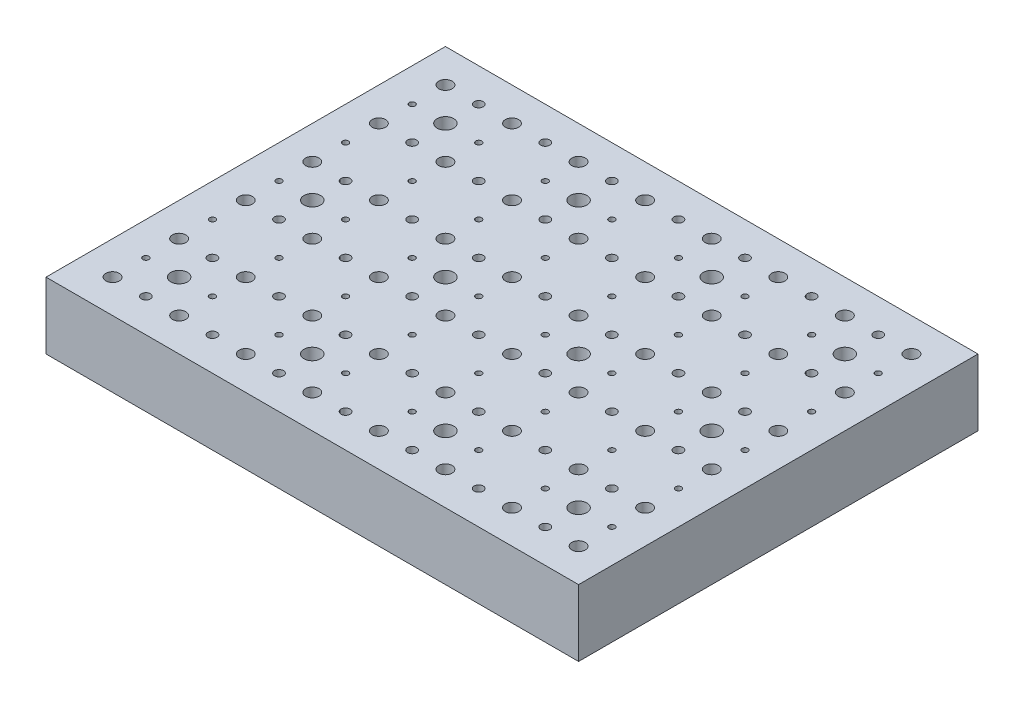
SolidWorks part; units mm, degrees
ref_plane "Front Plane" through (0, 0, 0) normal (0, 0, 1) x (1, 0, 0)
ref_plane "Top Plane" through (0, 0, 0) normal (0, 1, 0) x (1, 0, 0)
ref_plane "Right Plane" through (0, 0, 0) normal (1, 0, 0) x (0, 0, -1)
sketch "Sketch1" plane through (0, 0, 0) normal (0, 1, 0) x (1, 0, 0)
  line L1 (101.6, -76.2) -> (-101.6, -76.2)
  line L2 (101.6, -76.2) -> (101.6, 76.2)
  line L3 (101.6, 76.2) -> (-101.6, 76.2)
  line L4 (-101.6, -76.2) -> (-101.6, 76.2)
  line L5 (101.6, -76.2) -> (-101.6, 76.2) construction
  line L6 (101.6, 76.2) -> (-101.6, -76.2) construction
  point P0 (0, 0)
  dimension "D1" = 203.2
  dimension "D2" = 152.4
extrude "Boss-Extrude1" add sketch "Sketch1" against normal blind 25.4
hole_wizard "1/4-20 Tapped Hole2" positions "Sketch2" profile "Sketch3" tap size "1/4-20" standard "ANSI Inch" end condition through all
sketch "Sketch2" plane through (0, 0, 0) normal (0, 1, 0) x (1, 0, 0)
  line L0 (-12.7, 12.7) -> (0, 0) construction
  line L1 (0, 0) -> (-12.7, -12.7) construction
  line L3 (12.7, 12.7) -> (0, 0) construction
  line L4 (0, 0) -> (12.7, -12.7) construction
  point P0 (-88.9, 63.5)
  point P9 (-63.5, 63.5)
  point P10 (-38.1, 63.5)
  point P11 (-12.7, 63.5)
  point P12 (12.7, 63.5)
  point P13 (38.1, 63.5)
  point P14 (63.5, 63.5)
  point P15 (88.9, 63.5)
  point P16 (-63.5, 38.1)
  point P17 (-38.1, 38.1)
  point P18 (-12.7, 38.1)
  point P19 (12.7, 38.1)
  point P20 (38.1, 38.1)
  point P21 (63.5, 38.1)
  point P22 (88.9, 38.1)
  point P23 (-63.5, 12.7)
  point P24 (-38.1, 12.7)
  point P25 (-12.7, 12.7)
  point P26 (12.7, 12.7)
  point P27 (38.1, 12.7)
  point P28 (63.5, 12.7)
  point P29 (88.9, 12.7)
  point P30 (-63.5, -12.7)
  point P31 (-38.1, -12.7)
  point P32 (-12.7, -12.7)
  point P33 (12.7, -12.7)
  point P34 (38.1, -12.7)
  point P35 (63.5, -12.7)
  point P36 (88.9, -12.7)
  point P37 (-63.5, -38.1)
  point P38 (-38.1, -38.1)
  point P39 (-12.7, -38.1)
  point P40 (12.7, -38.1)
  point P41 (38.1, -38.1)
  point P42 (63.5, -38.1)
  point P43 (88.9, -38.1)
  point P44 (-63.5, -63.5)
  point P45 (-38.1, -63.5)
  point P46 (-12.7, -63.5)
  point P47 (12.7, -63.5)
  point P48 (38.1, -63.5)
  point P49 (63.5, -63.5)
  point P50 (88.9, -63.5)
  point P51 (-88.9, 38.1)
  point P52 (-88.9, 12.7)
  point P53 (-88.9, -12.7)
  point P54 (-88.9, -38.1)
  point P55 (-88.9, -63.5)
  dimension "D3" = 25.4
  dimension "D4" = 25.4
  dimension "D1" = 8
  dimension "D2" = 6
sketch "Sketch3" plane through (-88.9, 0, -63.5) normal (1, 0, 0) x (0, 0, 1)
  line L0 (0, 0) -> (0, 25.4)
  line L1 (0, 25.4) -> (2.5527, 25.4)
  line L2 (2.5527, 25.4) -> (2.5527, 0)
  line L5 (2.5527, 0) -> (0, 0)
  line L11 (0, -6.35) -> (0, 107.95) construction
  dimension "Thru Tap Drill Dia." = 5.1054
  dimension "Thru Tap Drill Depth" = 25.4
cosmetic thread "Hole Thread1" parameters "D2"=6.35
cosmetic thread "Hole Thread2" parameters "D2"=6.35
cosmetic thread "Hole Thread3" parameters "D2"=6.35
cosmetic thread "Hole Thread4" parameters "D2"=6.35
cosmetic thread "Hole Thread5" parameters "D2"=6.35
cosmetic thread "Hole Thread6" parameters "D2"=6.35
cosmetic thread "Hole Thread7" parameters "D2"=6.35
cosmetic thread "Hole Thread8" parameters "D2"=6.35
cosmetic thread "Hole Thread9" parameters "D2"=6.35
cosmetic thread "Hole Thread10" parameters "D2"=6.35
cosmetic thread "Hole Thread11" parameters "D2"=6.35
cosmetic thread "Hole Thread12" parameters "D2"=6.35
cosmetic thread "Hole Thread13" parameters "D2"=6.35
cosmetic thread "Hole Thread14" parameters "D2"=6.35
cosmetic thread "Hole Thread15" parameters "D2"=6.35
cosmetic thread "Hole Thread16" parameters "D2"=6.35
cosmetic thread "Hole Thread17" parameters "D2"=6.35
cosmetic thread "Hole Thread18" parameters "D2"=6.35
cosmetic thread "Hole Thread19" parameters "D2"=6.35
cosmetic thread "Hole Thread20" parameters "D2"=6.35
cosmetic thread "Hole Thread21" parameters "D2"=6.35
cosmetic thread "Hole Thread22" parameters "D2"=6.35
cosmetic thread "Hole Thread23" parameters "D2"=6.35
cosmetic thread "Hole Thread24" parameters "D2"=6.35
cosmetic thread "Hole Thread25" parameters "D2"=6.35
cosmetic thread "Hole Thread26" parameters "D2"=6.35
cosmetic thread "Hole Thread27" parameters "D2"=6.35
cosmetic thread "Hole Thread28" parameters "D2"=6.35
cosmetic thread "Hole Thread29" parameters "D2"=6.35
cosmetic thread "Hole Thread30" parameters "D2"=6.35
cosmetic thread "Hole Thread31" parameters "D2"=6.35
cosmetic thread "Hole Thread32" parameters "D2"=6.35
cosmetic thread "Hole Thread33" parameters "D2"=6.35
cosmetic thread "Hole Thread34" parameters "D2"=6.35
cosmetic thread "Hole Thread35" parameters "D2"=6.35
cosmetic thread "Hole Thread36" parameters "D2"=6.35
cosmetic thread "Hole Thread37" parameters "D2"=6.35
cosmetic thread "Hole Thread38" parameters "D2"=6.35
cosmetic thread "Hole Thread39" parameters "D2"=6.35
cosmetic thread "Hole Thread40" parameters "D2"=6.35
cosmetic thread "Hole Thread41" parameters "D2"=6.35
cosmetic thread "Hole Thread42" parameters "D2"=6.35
cosmetic thread "Hole Thread43" parameters "D2"=6.35
cosmetic thread "Hole Thread44" parameters "D2"=6.35
cosmetic thread "Hole Thread45" parameters "D2"=6.35
cosmetic thread "Hole Thread46" parameters "D2"=6.35
cosmetic thread "Hole Thread47" parameters "D2"=6.35
cosmetic thread "Hole Thread48" parameters "D2"=6.35
hole_wizard "#8-32 Tapped Hole1" positions "Sketch5" profile "Sketch6" tap size "#8-32" standard "ANSI Inch" end condition through all
sketch "Sketch5" plane through (0, 0, 0) normal (0, 1, 0) x (1, 0, 0)
  line L0 (-88.9, 63.5) -> (-76.2, 63.5) construction
  line L1 (-76.2, 63.5) -> (-63.5, 63.5) construction
  line L3 (-88.9, 38.1) -> (-76.2, 38.1) construction
  line L4 (-76.2, 38.1) -> (-63.5, 38.1) construction
  point P0 (-76.2, 63.5)
  point P8 (-50.8, 63.5)
  point P9 (-25.4, 63.5)
  point P10 (0, 63.5)
  point P11 (25.4, 63.5)
  point P12 (50.8, 63.5)
  point P13 (76.2, 63.5)
  point P14 (-50.8, 38.1)
  point P15 (-25.4, 38.1)
  point P16 (0, 38.1)
  point P17 (25.4, 38.1)
  point P18 (50.8, 38.1)
  point P19 (76.2, 38.1)
  point P20 (-50.8, 12.7)
  point P21 (-25.4, 12.7)
  point P22 (0, 12.7)
  point P23 (25.4, 12.7)
  point P24 (50.8, 12.7)
  point P25 (76.2, 12.7)
  point P26 (-50.8, -12.7)
  point P27 (-25.4, -12.7)
  point P28 (0, -12.7)
  point P29 (25.4, -12.7)
  point P30 (50.8, -12.7)
  point P31 (76.2, -12.7)
  point P32 (-50.8, -38.1)
  point P33 (-25.4, -38.1)
  point P34 (0, -38.1)
  point P35 (25.4, -38.1)
  point P36 (50.8, -38.1)
  point P37 (76.2, -38.1)
  point P38 (-50.8, -63.5)
  point P39 (-25.4, -63.5)
  point P40 (0, -63.5)
  point P41 (25.4, -63.5)
  point P42 (50.8, -63.5)
  point P43 (76.2, -63.5)
  point P44 (-76.2, 38.1)
  point P45 (-76.2, 12.7)
  point P46 (-76.2, -12.7)
  point P47 (-76.2, -38.1)
  point P48 (-76.2, -63.5)
  point P63 (0, 0)
  dimension "D3" = 25.4
  dimension "D1" = 7
  dimension "D2" = 6
sketch "Sketch6" plane through (-76.2, 0, -63.5) normal (1, 0, 0) x (0, 0, 1)
  line L0 (0, 0) -> (0, 25.4)
  line L1 (0, 25.4) -> (1.7272, 25.4)
  line L2 (1.7272, 25.4) -> (1.7272, 0)
  line L5 (1.7272, 0) -> (0, 0)
  line L11 (0, -6.35) -> (0, 107.95) construction
  dimension "Thru Tap Drill Dia." = 3.4544
  dimension "Thru Tap Drill Depth" = 25.4
cosmetic thread "Hole Thread49"
cosmetic thread "Hole Thread50"
cosmetic thread "Hole Thread51"
cosmetic thread "Hole Thread52"
cosmetic thread "Hole Thread53"
cosmetic thread "Hole Thread54"
cosmetic thread "Hole Thread55"
cosmetic thread "Hole Thread56"
cosmetic thread "Hole Thread57"
cosmetic thread "Hole Thread58"
cosmetic thread "Hole Thread59"
cosmetic thread "Hole Thread60"
cosmetic thread "Hole Thread61"
cosmetic thread "Hole Thread62"
cosmetic thread "Hole Thread63"
cosmetic thread "Hole Thread64"
cosmetic thread "Hole Thread65"
cosmetic thread "Hole Thread66"
cosmetic thread "Hole Thread67"
cosmetic thread "Hole Thread68"
cosmetic thread "Hole Thread69"
cosmetic thread "Hole Thread70"
cosmetic thread "Hole Thread71"
cosmetic thread "Hole Thread72"
cosmetic thread "Hole Thread73"
cosmetic thread "Hole Thread74"
cosmetic thread "Hole Thread75"
cosmetic thread "Hole Thread76"
cosmetic thread "Hole Thread77"
cosmetic thread "Hole Thread78"
cosmetic thread "Hole Thread79"
cosmetic thread "Hole Thread80"
cosmetic thread "Hole Thread81"
cosmetic thread "Hole Thread82"
cosmetic thread "Hole Thread83"
cosmetic thread "Hole Thread84"
cosmetic thread "Hole Thread85"
cosmetic thread "Hole Thread86"
cosmetic thread "Hole Thread87"
cosmetic thread "Hole Thread88"
cosmetic thread "Hole Thread89"
cosmetic thread "Hole Thread90"
hole_wizard "#4-40 Tapped Hole1" positions "Sketch7" profile "Sketch8" tap size "#4-40" standard "ANSI Inch" end condition through all
sketch "Sketch7" plane through (0, 0, 0) normal (0, 1, 0) x (1, 0, 0)
  line L0 (-88.9, 63.5) -> (-88.9, 50.8) construction
  line L1 (-88.9, 50.8) -> (-88.9, 38.1) construction
  point P0 (-88.9, 50.8)
  point P17 (-63.5, 50.8)
  point P18 (-38.1, 50.8)
  point P19 (-12.7, 50.8)
  point P20 (12.7, 50.8)
  point P21 (38.1, 50.8)
  point P22 (63.5, 50.8)
  point P23 (88.9, 50.8)
  point P24 (-63.5, 25.4)
  point P25 (-38.1, 25.4)
  point P26 (-12.7, 25.4)
  point P27 (12.7, 25.4)
  point P28 (38.1, 25.4)
  point P29 (63.5, 25.4)
  point P30 (88.9, 25.4)
  point P31 (-63.5, 0)
  point P32 (-38.1, 0)
  point P33 (-12.7, 0)
  point P34 (12.7, 0)
  point P35 (38.1, 0)
  point P36 (63.5, 0)
  point P37 (88.9, 0)
  point P38 (-63.5, -25.4)
  point P39 (-38.1, -25.4)
  point P40 (-12.7, -25.4)
  point P41 (12.7, -25.4)
  point P42 (38.1, -25.4)
  point P43 (63.5, -25.4)
  point P44 (88.9, -25.4)
  point P45 (-63.5, -50.8)
  point P46 (-38.1, -50.8)
  point P47 (-12.7, -50.8)
  point P48 (12.7, -50.8)
  point P49 (38.1, -50.8)
  point P50 (63.5, -50.8)
  point P51 (88.9, -50.8)
  point P52 (-88.9, 25.4)
  point P53 (-88.9, 0)
  point P54 (-88.9, -25.4)
  point P55 (-88.9, -50.8)
  point P56 (0, 0)
  point P57 (0, 0)
  dimension "D3" = 25.4
  dimension "D4" = 25.4
  dimension "D1" = 8
  dimension "D2" = 5
sketch "Sketch8" plane through (-88.9, 0, -50.8) normal (1, 0, 0) x (0, 0, 1)
  line L0 (0, 0) -> (0, 25.4)
  line L1 (0, 25.4) -> (1.1303, 25.4)
  line L2 (1.1303, 25.4) -> (1.1303, 0)
  line L5 (1.1303, 0) -> (0, 0)
  line L11 (0, -6.35) -> (0, 107.95) construction
  dimension "Thru Tap Drill Dia." = 2.2606
  dimension "Thru Tap Drill Depth" = 25.4
cosmetic thread "Hole Thread91"
cosmetic thread "Hole Thread92"
cosmetic thread "Hole Thread93"
cosmetic thread "Hole Thread94"
cosmetic thread "Hole Thread95"
cosmetic thread "Hole Thread96"
cosmetic thread "Hole Thread97"
cosmetic thread "Hole Thread98"
cosmetic thread "Hole Thread99"
cosmetic thread "Hole Thread100"
cosmetic thread "Hole Thread101"
cosmetic thread "Hole Thread102"
cosmetic thread "Hole Thread103"
cosmetic thread "Hole Thread104"
cosmetic thread "Hole Thread105"
cosmetic thread "Hole Thread106"
cosmetic thread "Hole Thread107"
cosmetic thread "Hole Thread108"
cosmetic thread "Hole Thread109"
cosmetic thread "Hole Thread110"
cosmetic thread "Hole Thread111"
cosmetic thread "Hole Thread112"
cosmetic thread "Hole Thread113"
cosmetic thread "Hole Thread114"
cosmetic thread "Hole Thread115"
cosmetic thread "Hole Thread116"
cosmetic thread "Hole Thread117"
cosmetic thread "Hole Thread118"
cosmetic thread "Hole Thread119"
cosmetic thread "Hole Thread120"
cosmetic thread "Hole Thread121"
cosmetic thread "Hole Thread122"
cosmetic thread "Hole Thread123"
cosmetic thread "Hole Thread124"
cosmetic thread "Hole Thread125"
cosmetic thread "Hole Thread126"
cosmetic thread "Hole Thread127"
cosmetic thread "Hole Thread128"
cosmetic thread "Hole Thread129"
cosmetic thread "Hole Thread130"
sketch "Sketch9" plane through (0, 0, 0) normal (0, 1, 0) x (1, 0, 0)
  line L0 (-88.9, 63.5) -> (-76.2, 50.8) construction
  line L1 (-76.2, 50.8) -> (-63.5, 38.1) construction
  circle A0 centre (-76.2, 50.8) radius 3.175
  circle A1 centre (-25.4, 50.8) radius 3.175
  circle A2 centre (25.4, 50.8) radius 3.175
  circle A3 centre (76.2, 50.8) radius 3.175
  circle A4 centre (-25.4, 0) radius 3.175
  circle A5 centre (25.4, 0) radius 3.175
  circle A6 centre (76.2, 0) radius 3.175
  circle A7 centre (-25.4, -50.8) radius 3.175
  circle A8 centre (25.4, -50.8) radius 3.175
  circle A9 centre (76.2, -50.8) radius 3.175
  circle A10 centre (-76.2, 0) radius 3.175
  circle A11 centre (-76.2, -50.8) radius 3.175
  point P7 (0, 0)
  point P8 (0, 0)
  dimension "D1" = 6.35
  dimension "D4" = 50.8
  dimension "D5" = 50.8
  dimension "D2" = 4
  dimension "D3" = 3
extrude "Bushings for 1/8'' dowel pins" cut sketch "Sketch9" against normal blind 12.7 contours A10
